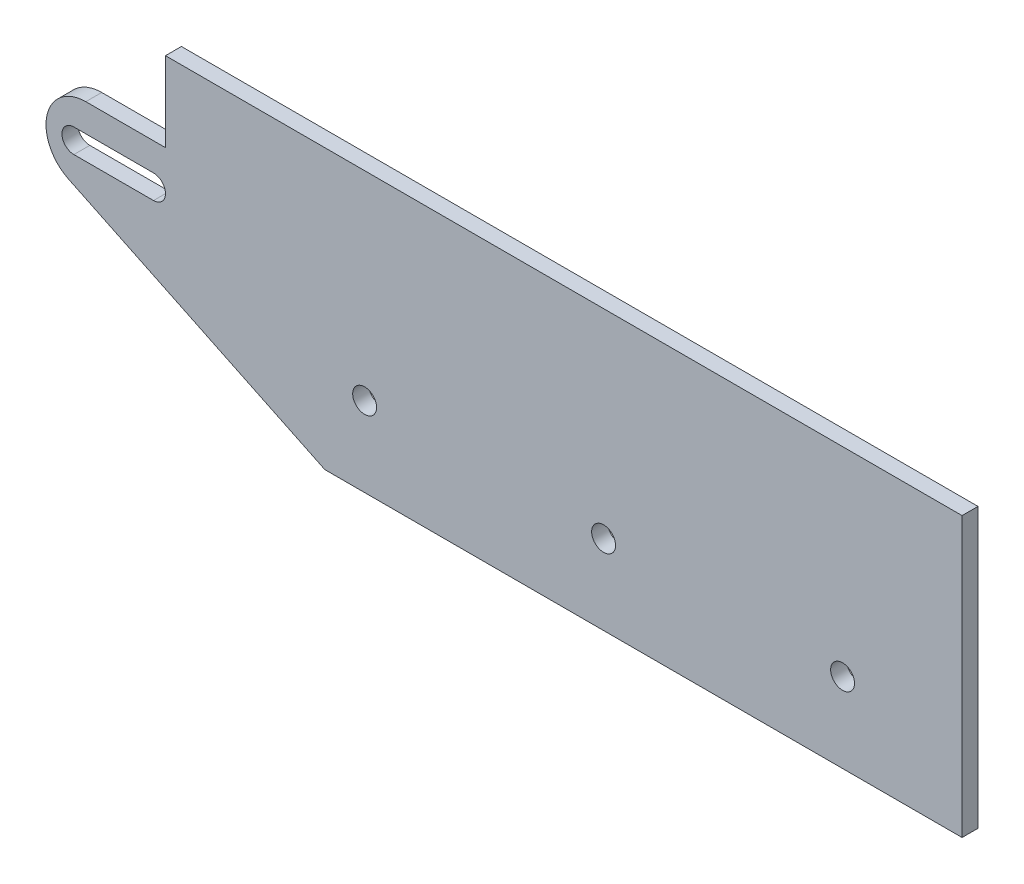
SolidWorks part; units mm, degrees
ref_plane "Ebene vorne" through (0, 0, 0) normal (0, 0, 1) x (1, 0, 0)
ref_plane "Ebene oben" through (0, 0, 0) normal (0, 1, 0) x (1, 0, 0)
ref_plane "Ebene rechts" through (0, 0, 0) normal (1, 0, 0) x (0, 0, -1)
sketch "Skizze1" plane through (0, 0, 0) normal (0, 0, 1) x (1, 0, 0)
  line L0 (-50, 7.5) -> (-60, 7.5)
  line L1 (50, -17.5) -> (-50, -17.5)
  line L2 (50, -17.5) -> (50, 17.5)
  line L3 (50, 17.5) -> (-50, 17.5)
  line L4 (-50, -17.5) -> (-50, 17.5)
  line L5 (50, -17.5) -> (-50, 17.5) construction
  line L6 (50, 17.5) -> (-50, -17.5) construction
  line L7 (-60, 7.5) -> (-60, -2.5)
  line L8 (-60, -2.5) -> (-50, -2.5)
  line L9 (-30, -17.5) -> (-62.1698, -2.0047)
  circle A0 centre (-60, 2.5) radius 5
  point P0 (0, 0)
  dimension "D3" = 10
  dimension "D1" = 100
  dimension "D2" = 35
  dimension "D4" = 10
  dimension "D5" = 20
  dimension "D6" = 10
extrude "Aufsatz-Linear austragen1" add sketch "Skizze1" along normal blind 2 contours L9 L1 L2 L3 L4 | A0 L8 L4 L0 | L7 A0 | L7 A0 | A0 L9 L4 L8
sketch "Skizze2" plane through (0, 0, 2) normal (0, 0, 1) x (1, 0, 0)
  line L0 (50, -17.5) -> (50, 17.5) construction
  line L1 (50, -17.5) -> (-30, -17.5) construction
  line L2 (-61.5, 4) -> (-51.5, 4)
  line L3 (-61.5, 1) -> (-51.5, 1)
  line L7 (-50, 7.5) -> (-60, 7.5) construction
  circle A0 centre (35, -7.5) radius 1.5
  circle A1 centre (5, -7.5) radius 1.5
  circle A2 centre (-25, -7.5) radius 1.5
  circle A3 centre (-61.5, 2.5) radius 1.5
  circle A4 centre (-51.5, 2.5) radius 1.5
  arc A6 (-60, 7.5) -> (-62.1698, -2.0047) centre (-60, 2.5) ccw construction
  dimension "D4" = 3
  dimension "D5" = 3
  dimension "D6" = 3
  dimension "D8" = 3
  dimension "D9" = 3
  dimension "D1" = 15
  dimension "D2" = 30
  dimension "D3" = 30
  dimension "D7" = 10
  dimension "D10" = 5
  dimension "D11" = 1.5
  dimension "D12" = 10
extrude "Schnitt-Linear austragen1" cut sketch "Skizze2" against normal through all contours A4 | A4 L2 A3 L3 | A3 | A2 | A0 | A1
